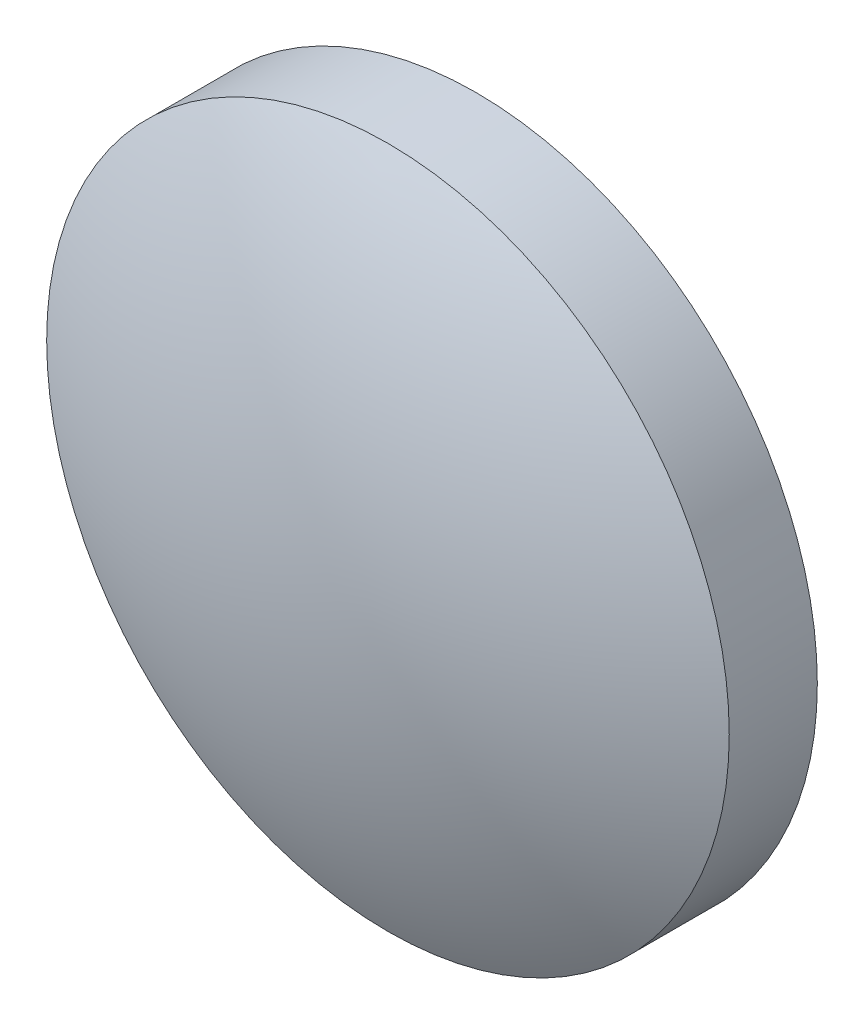
SolidWorks part; units mm, degrees
ref_plane "Front Plane" through (0, 0, 0) normal (0, 0, 1) x (1, 0, 0)
ref_plane "Top Plane" through (0, 0, 0) normal (0, 1, 0) x (1, 0, 0)
ref_plane "Right Plane" through (0, 0, 0) normal (1, 0, 0) x (0, 0, -1)
sketch "Sketch3" plane through (0, 0, 0) normal (1, 0, 0) x (0, 0, -1)
  line L0 (-1.4428, 0) -> (1.4428, 0)
  line L1 (0, 0) -> (0, 3.875)
  line L2 (-0.5, 3.875) -> (0.5, 3.875)
  line L3 (0, 0) -> (-6.9922, 0)
  arc A0 (1.4428, 0) -> (0.5, 3.875) centre (-6.9922, 0) ccw
  arc A1 (-1.4428, 0) -> (-0.5, 3.875) centre (6.9922, 0) cw
  dimension "D1" = 1.4428
  dimension "D2" = 3.875
  dimension "D3" = 0.5
  dimension "D4" = 6.9922
revolve "Revolve1" add sketch "Sketch3" angle 360 about L3
equation "\"T_edge\" = \"gloabl_scale\" * 1mm"
equation "\"R\"= \"gloabl_scale\" * 8.435mm"
equation "\"dT_c\"= \"R\" * ( 1 - sqr ( 1 - \"h\" ^ 2 / \"R\" ^ 2 ) )"
equation "\"h\"= \"gloabl_scale\" * 7.75 / 2mm"
equation "\"gloabl_scale\"= 1"
equation "\"x_sphere_origin\"= \"R\" - \"dT_c\" - \"T_edge\" / 2"
equation "\"T_c\"= \"T_edge\" + 2 * \"dT_c\""
equation "\"D1@Sketch3\"=\"T_c\" / 2"
equation "\"D2@Sketch3\"=\"h\""
equation "\"D3@Sketch3\"=\"T_edge\" / 2"
equation "\"D4@Sketch3\"=\"x_sphere_origin\""
